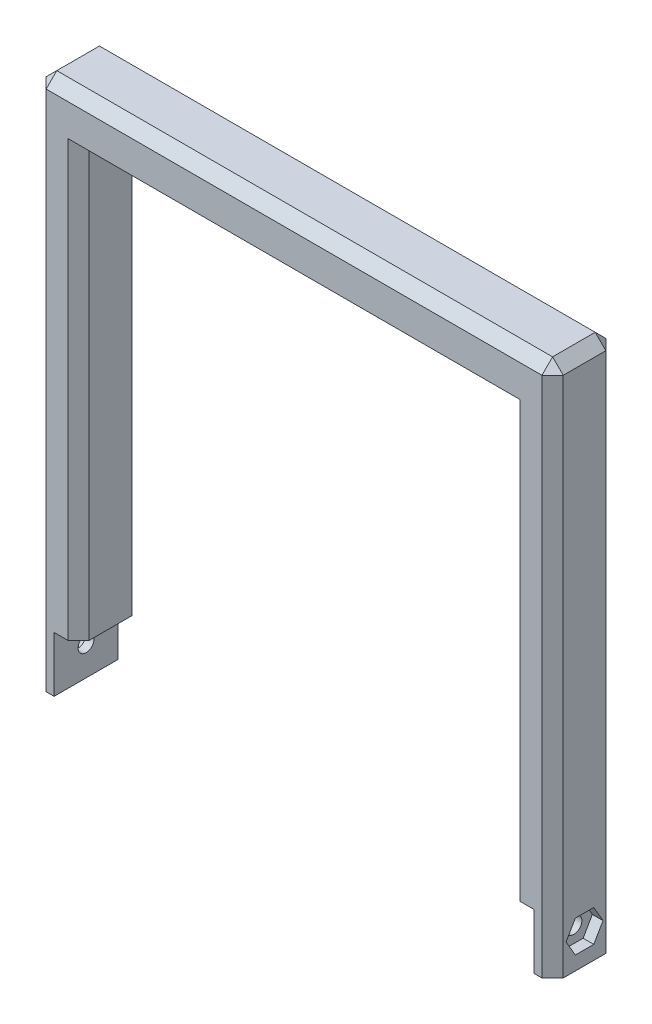
SolidWorks part; units mm, degrees
ref_plane "Front Plane" through (0, 0, 0) normal (0, 0, 1) x (1, 0, 0)
ref_plane "Top Plane" through (0, 0, 0) normal (0, 1, 0) x (1, 0, 0)
ref_plane "Right Plane" through (0, 0, 0) normal (1, 0, 0) x (0, 0, -1)
sketch "Sketch1" plane through (0, 0, 0) normal (0, 1, 0) x (1, 0, 0)
  line L0 (-45.0441, 0) -> (45.0441, 0) construction
  line L1 (-45.0441, 6) -> (-45.0441, -6)
  line L2 (-45.0441, -6) -> (-48.5441, -6)
  line L3 (-48.5441, -6) -> (-48.5441, 6)
  line L4 (-48.5441, 6) -> (-45.0441, 6)
  line L5 (0, -55) -> (0, 55) construction
  line L6 (48.5441, -6) -> (48.5441, 6)
  line L7 (45.0441, -6) -> (48.5441, -6)
  line L8 (45.0441, 6) -> (45.0441, -6)
  line L9 (48.5441, 6) -> (45.0441, 6)
  point P4 (0, 0)
  dimension "D1" = 12
  dimension "D2" = 6
  dimension "D3" = 3.5
  dimension "D4" = 45.0441
extrude "Boss-Extrude1" add sketch "Sketch1" along normal blind 100
sketch "Sketch2" plane through (-45.0441, 0, 0) normal (1, 0, 0) x (0, 0, -1)
  line L0 (-6, 100) -> (-6, 90)
  line L1 (-6, 100) -> (-6, 0) construction
  line L2 (-6, 90) -> (6, 90)
  line L3 (6, 100) -> (6, 0) construction
  line L4 (6, 90) -> (6, 100)
  line L5 (6, 100) -> (-6, 100)
  dimension "D1" = 10
extrude "Boss-Extrude2" add sketch "Sketch2" along normal up to surface (90.0883 mm away) up to face at (45.0441, 50, 0)
sketch "Sketch3" plane through (0, 90, 0) normal (0, -1, 0) x (1, 0, 0)
  line L0 (-45.0441, 6) -> (-40.4585, 6)
  line L1 (45.0441, 6) -> (-45.0441, 6) construction
  line L2 (-40.4585, 6) -> (-40.4585, -6)
  line L3 (45.0441, -6) -> (-45.0441, -6) construction
  line L4 (-40.4585, -6) -> (-45.0441, -6)
  line L5 (-45.0441, -6) -> (-45.0441, 6)
  line L6 (45.0441, 6) -> (40.4585, 6)
  line L7 (40.4585, 6) -> (40.4585, -6)
  line L8 (40.4585, -6) -> (45.0441, -6)
  line L9 (45.0441, -6) -> (45.0441, 6)
  dimension "D1" = 4.5856
  dimension "D2" = 4.5856
extrude "Boss-Extrude3" add sketch "Sketch3" along normal blind 79.6
chamfer "Chamfer6" distance 2 angle 45 14 edges at (48.5441, 100, 0) (48.5441, 50, -6) (0, 100, -6) (-48.5441, 50, -6) (-48.5441, 100, 0) (-48.5441, 50, 6) (0, 100, 6) (48.5441, 50, 6) (40.4585, 50.2, -6) (0, 90, -6) (-40.4585, 50.2, -6) (40.4585, 50.2, 6) (0, 90, 6) (-40.4585, 50.2, 6)
sketch "Sketch4" plane through (48.5441, 0, 0) normal (1, 0, 0) x (0, 0, -1)
  line L0 (-4, 0) -> (4, 0) construction
  line L1 (3.4641, 5.6) -> (1.7321, 8.6)
  line L2 (1.7321, 8.6) -> (-1.7321, 8.6)
  line L3 (-1.7321, 8.6) -> (-3.4641, 5.6)
  line L4 (-3.4641, 5.6) -> (-1.7321, 2.6)
  line L5 (-1.7321, 2.6) -> (1.7321, 2.6)
  line L6 (1.7321, 2.6) -> (3.4641, 5.6)
  circle A0 centre (0, 5.6) radius 3 construction
  point P1 (0, 0)
  point P10 (0, 0)
  dimension "D1" = 6
  dimension "D2" = 5.6
extrude "Cut-Extrude1" cut sketch "Sketch4" against normal blind 2
mirror "Mirror1" about plane through (0, 0, 0) normal (1, 0, 0) of "Cut-Extrude1"
sketch "Sketch5" plane through (46.5441, 0, 0) normal (1, 0, 0) x (0, 0, -1)
  line L0 (-4, 0) -> (4, 0) construction
  circle A0 centre (0, 5.6) radius 1.5
  point P4 (0, 0)
  dimension "D1" = 3
  dimension "D2" = 5.6
extrude "Cut-Extrude2" cut sketch "Sketch5" against normal up to surface (93.0883 mm away) up to face at (-46.5441, 5.6, 0)
